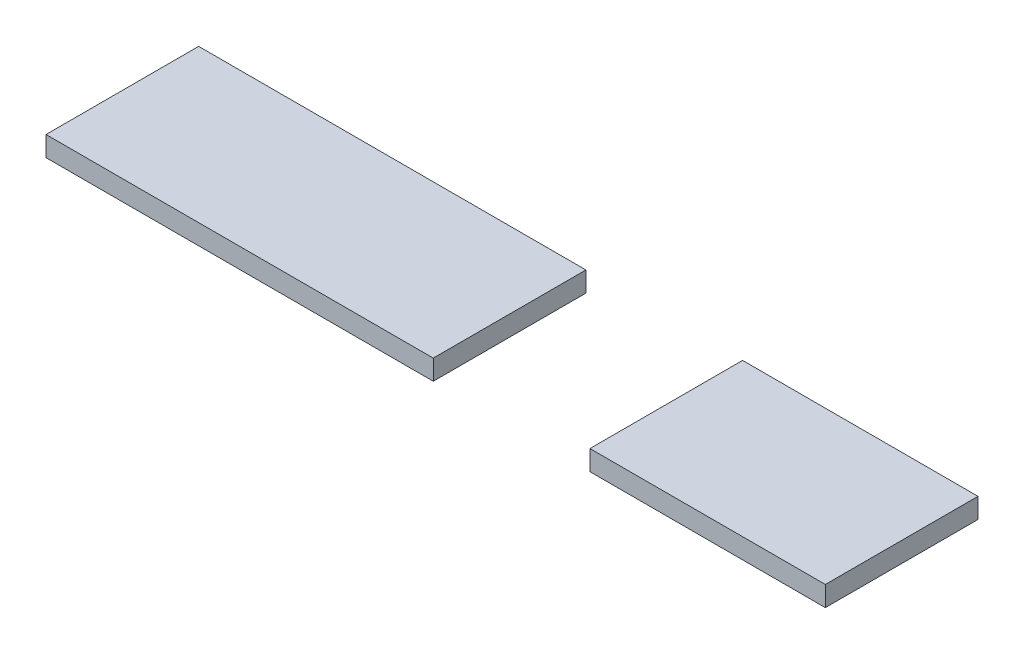
SolidWorks part; units mm, degrees
ref_plane "Front Plane" through (0, 0, 0) normal (0, 0, 1) x (1, 0, 0)
ref_plane "Top Plane" through (0, 0, 0) normal (0, 1, 0) x (1, 0, 0)
ref_plane "Right Plane" through (0, 0, 0) normal (1, 0, 0) x (0, 0, -1)
sketch "Sketch1" plane through (0, 0, 0) normal (0, 1, 0) x (1, 0, 0)
  line L1 (-101.2488, 19) -> (-53.0488, 19)
  line L2 (-101.2488, 19) -> (-101.2488, 0)
  line L3 (-101.2488, 0) -> (-53.0488, 0)
  line L4 (-53.0488, 19) -> (-53.0488, 0)
  line L5 (-33.5488, 19) -> (-4.2488, 19)
  line L6 (-33.5488, 19) -> (-33.5488, 0)
  line L7 (-33.5488, 0) -> (-4.2488, 0)
  line L8 (-4.2488, 19) -> (-4.2488, 0)
  point P8 (-33.5488, 9.5)
  dimension "D1" = 48.2
  dimension "D2" = 19
  dimension "D3" = 29.3
  dimension "D4" = 19
  dimension "D5" = 19.5
extrude "Boss-Extrude1" add sketch "Sketch1" along normal blind 2.5
